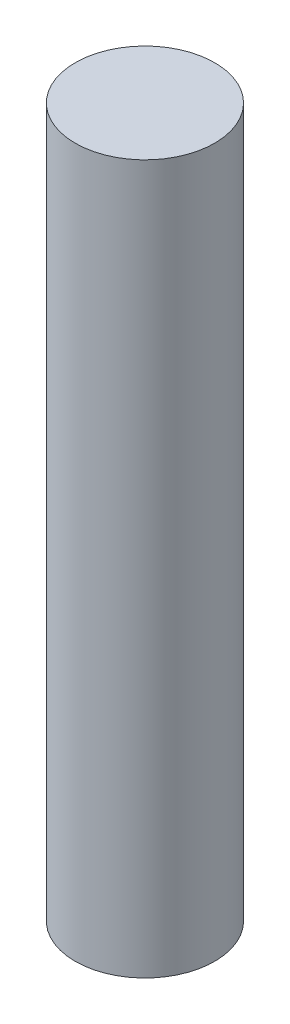
SolidWorks part; units mm, degrees
material "1023 Carbon Steel Sheet (SS)"
ref_plane "Front Plane" through (0, 0, 0) normal (0, 0, 1) x (1, 0, 0)
ref_plane "Top Plane" through (0, 0, 0) normal (0, 1, 0) x (1, 0, 0)
ref_plane "Right Plane" through (0, 0, 0) normal (1, 0, 0) x (0, 0, -1)
sketch "Sketch1" plane through (0, 0, 0) normal (0, 1, 0) x (1, 0, 0)
  circle A0 centre (0, 0) radius 3
  dimension "D1" = 6
extrude "Boss-Extrude1" add sketch "Sketch1" against normal blind 30.48 from offset 65.278 contours A0 offset against normal yes
